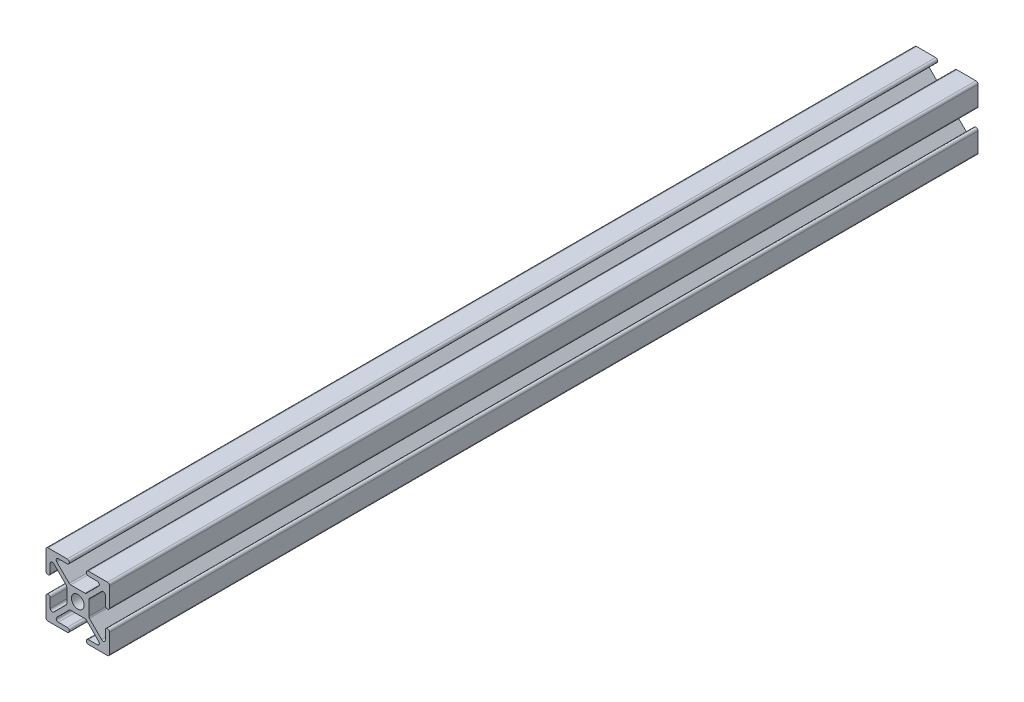
SolidWorks part; units mm, degrees
ref_plane "Alzado" through (0, 0, 0) normal (0, 0, 1) x (1, 0, 0)
ref_plane "Planta" through (0, 0, 0) normal (0, 1, 0) x (1, 0, 0)
ref_plane "Vista lateral" through (0, 0, 0) normal (1, 0, 0) x (0, 0, -1)
sketch "Croquis1" plane through (0, 0, 0) normal (0, 0, 1) x (1, 0, 0)
  line L1 (-14, 15) -> (14, 15)
  line L2 (-15, 14) -> (-15, -14)
  line L3 (-14, -15) -> (14, -15)
  line L4 (15, 14) -> (15, -14)
  line L5 (-15, 15) -> (15, -15) construction
  line L6 (-15, -15) -> (15, 15) construction
  arc A0 (-14, 15) -> (-15, 14) centre (-14, 14) ccw
  arc A1 (14, -15) -> (15, -14) centre (14, -14) ccw
  arc A2 (-14, -15) -> (-15, -14) centre (-14, -14) cw
  arc A3 (15, 14) -> (14, 15) centre (14, 14) ccw
  point P0 (0, 0)
  dimension "D3" = 1
  dimension "D4" = 1
  dimension "D1" = 30
  dimension "D2" = 30
extrude "Saliente-Extruir1" add sketch "Croquis1" against normal blind 410
sketch "Croquis2" plane through (0, 0, 0) normal (0, 0, 1) x (1, 0, 0)
  circle A0 centre (0, 0) radius 3
  dimension "D1" = 6
sketch "Croquis3" plane through (0, 0, 0) normal (0, 0, 1) x (1, 0, 0)
  line L0 (-15, 0) -> (15, 0) construction
  line L1 (4.0787, -5.4929) -> (9.8787, -11.2929)
  line L2 (-11.2929, 9.8787) -> (-5.4929, 4.0787)
  line L3 (-9.8787, 11.2929) -> (-4.0787, 5.4929)
  line L4 (-13, 9.1716) -> (-13, 5)
  line L5 (-15, 14) -> (-15, -14) construction
  line L6 (-5.2, 3.3716) -> (-5.2, -3.3716)
  line L7 (-9.1716, 13) -> (-5, 13)
  line L8 (9.8787, 11.2929) -> (4.0787, 5.4929)
  line L9 (11.2929, 9.8787) -> (5.4929, 4.0787)
  line L10 (-3.3716, 5.2) -> (3.3716, 5.2)
  line L11 (14, 15) -> (-14, 15) construction
  line L12 (13, 9.1716) -> (13, 5)
  line L13 (5.2, 3.3716) -> (5.2, -3.3716)
  line L14 (15, -14) -> (15, 14) construction
  line L15 (-9.1716, -13) -> (-5, -13)
  line L16 (-3.3716, -5.2) -> (3.3716, -5.2)
  line L17 (-14, -15) -> (14, -15) construction
  line L18 (-5.4929, -4.0787) -> (-11.2929, -9.8787)
  line L19 (5.4929, -4.0787) -> (11.2929, -9.8787)
  line L20 (-4.0787, -5.4929) -> (-9.8787, -11.2929)
  line L21 (5, -13) -> (9.1716, -13)
  line L22 (-13, -5) -> (-13, -9.1716)
  line L23 (13, -5) -> (13, -9.1716)
  line L24 (0, 15) -> (0, -5.2) construction
  line L34 (5, 13) -> (9.1716, 13)
  arc A0 (9.8787, 11.2929) -> (9.1716, 13) centre (9.1716, 12) ccw
  arc A1 (-9.8787, 11.2929) -> (-9.1716, 13) centre (-9.1716, 12) cw
  arc A2 (9.8787, 11.2929) -> (9.1716, 13) centre (9.1716, 12) ccw
  arc A3 (13, 9.1716) -> (11.2929, 9.8787) centre (12, 9.1716) ccw
  arc A4 (11.2929, -9.8787) -> (13, -9.1716) centre (12, -9.1716) ccw
  arc A5 (9.1716, -13) -> (9.8787, -11.2929) centre (9.1716, -12) ccw
  arc A6 (-9.1716, -13) -> (-9.8787, -11.2929) centre (-9.1716, -12) cw
  arc A7 (-11.2929, -9.8787) -> (-13, -9.1716) centre (-12, -9.1716) cw
  arc A8 (-13, 9.1716) -> (-11.2929, 9.8787) centre (-12, 9.1716) cw
  arc A9 (-4.0787, -5.4929) -> (-3.3716, -5.2) centre (-3.3716, -6.2) cw
  arc A10 (3.3716, -5.2) -> (4.0787, -5.4929) centre (3.3716, -6.2) cw
  arc A11 (5.4929, -4.0787) -> (5.2, -3.3716) centre (6.2, -3.3716) cw
  arc A12 (5.2, 3.3716) -> (5.4929, 4.0787) centre (6.2, 3.3716) cw
  arc A13 (3.3716, 5.2) -> (4.0787, 5.4929) centre (3.3716, 6.2) ccw
  arc A14 (-3.3716, 5.2) -> (-4.0787, 5.4929) centre (-3.3716, 6.2) cw
  arc A15 (-5.4929, -4.0787) -> (-5.2, -3.3716) centre (-6.2, -3.3716) ccw
  arc A16 (-5.2, 3.3716) -> (-5.4929, 4.0787) centre (-6.2, 3.3716) ccw
  circle A17 centre (-14, -5) radius 1
  circle A18 centre (-14, 5) radius 1
  circle A19 centre (-5, -14) radius 1
  circle A20 centre (5, -14) radius 1
  circle A21 centre (14, 5) radius 1
  circle A22 centre (14, -5) radius 1
  circle A23 centre (-5, 14) radius 1
  circle A24 centre (5, 14) radius 1
  point P20 (-11.5858, -13)
  point P30 (-13, -11.5858)
  point P43 (-3.7858, -5.2)
  point P50 (3.7858, -5.2)
  point P53 (5.2, -3.7858)
  point P62 (-5.2, -3.7858)
  line M2 (-15, 14) -> (-15, -14)
  line M4 (-14, -15) -> (14, -15)
  line M6 (15, -14) -> (15, 14)
  line M8 (14, 15) -> (-14, 15)
  dimension "D6" = 9.8
  dimension "D7" = 2
  dimension "D12" = 2
  dimension "D19" = 1
  dimension "D2" = 1
  dimension "D3" = 1
  dimension "D4" = 1
  dimension "D16" = 1
  dimension "D5" = 2
  dimension "D8" = 9.8
  dimension "D9" = 2
  dimension "D10" = 9.8
  dimension "D11" = 9.8
  dimension "D15" = 1
  dimension "D20" = 1
  dimension "D23" = 1
  dimension "D24" = 1
  dimension "D27" = 1
  dimension "D28" = 1
extrude "Cortar-Extruir1" cut sketch "Croquis2" against normal through all
extrude "Cortar-Extruir3" cut sketch "Croquis3" against normal through all contours A18 A17 L22 A7 L18 A15 L6 A16 L2 A8 L4 M2 | A24 A23 L7 A1 L3 A14 L10 A13 L8 A0 L34 M8 | A20 L21 A5 L1 A10 L16 A9 L20 A6 L15 A19 M4 | A22 A21 L12 A3 L9 A12 L13 A11 L19 A4 L23 M6
